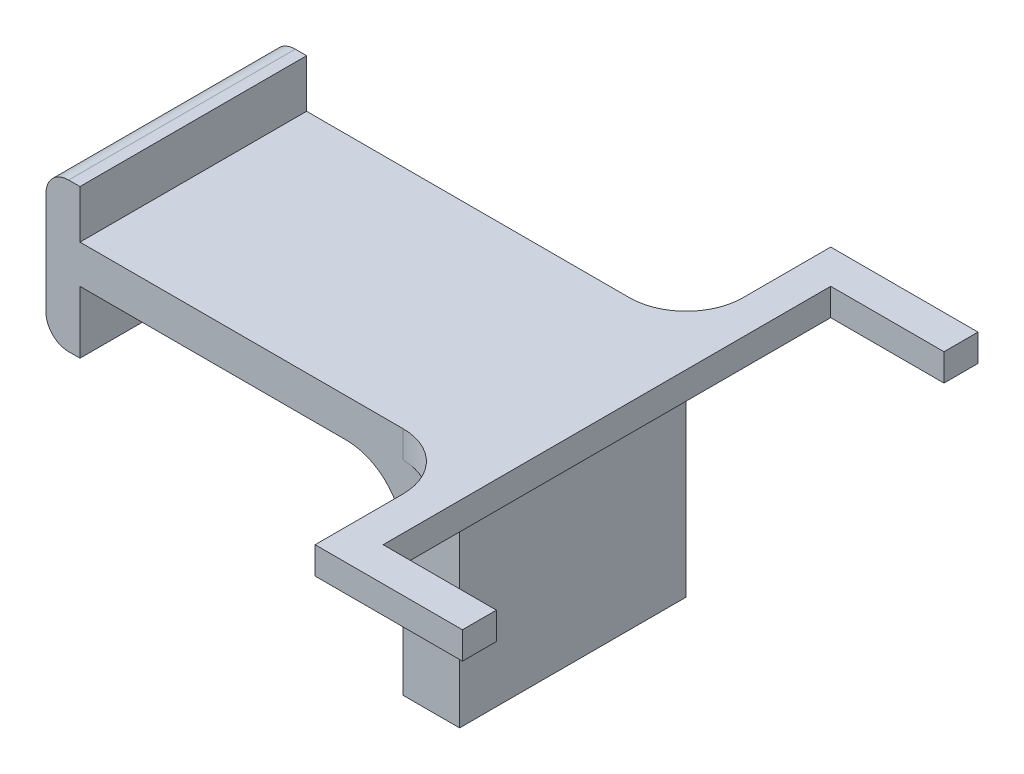
SolidWorks part; units mm, degrees
ref_plane "Front Plane" through (0, 0, 0) normal (0, 0, 1) x (1, 0, 0)
ref_plane "Top Plane" through (0, 0, 0) normal (0, 1, 0) x (1, 0, 0)
ref_plane "Right Plane" through (0, 0, 0) normal (1, 0, 0) x (0, 0, -1)
sketch "Sketch1" plane through (0, 0, 0) normal (0, 1, 0) x (1, 0, 0)
  line L0 (0, 19.75) -> (0, 22.75)
  line L1 (0, 22.75) -> (-13, 22.75)
  line L2 (-13, 22.75) -> (-13, -22.75)
  line L3 (-13, -22.75) -> (0, -22.75)
  line L4 (0, -22.75) -> (0, -19.75)
  line L5 (0, -19.75) -> (-10, -19.75)
  line L6 (-10, -19.75) -> (-10, 19.75)
  line L7 (-10, 19.75) -> (0, 19.75)
  line L9 (-13, 10) -> (-46.5, 10)
  line L10 (-13, 10) -> (-13, -10)
  line L11 (-13, -10) -> (-46.5, -10)
  line L12 (-46.5, 10) -> (-46.5, -10)
  point P7 (-10, 0)
  point P10 (-13, 0)
  dimension "D1" = 45.5
  dimension "D2" = 13
  dimension "D3" = 3
  dimension "D4" = 3
  dimension "D5" = 3
  dimension "D6" = 36.5
  dimension "D7" = 20
extrude "Boss-Extrude1" add sketch "Sketch1" against normal blind 2.4 contours L9 L12 L11 L2 | L6 L7 L0 L1 L2 L3 L4 L5
sketch "Sketch3" plane through (0, 0, 0) normal (0, 0, 1) x (1, 0, 0)
  line L0 (-13, -2.4) -> (-13, -20.38)
  line L1 (-13, -20.38) -> (-18, -20.38)
  line L2 (-18, -20.38) -> (-18, -3.38)
  line L3 (-46.5, -3.38) -> (-46.5, -8.875)
  line L4 (-46.5, -8.875) -> (-49.5, -8.875)
  line L5 (-49.5, -8.875) -> (-49.5, 4.25)
  line L6 (-49.5, 4.25) -> (-46.5, 4.25)
  line L7 (-46.5, 4.25) -> (-46.5, -2.4)
  line L8 (-46.5, -2.4) -> (-13, -2.4)
  line L9 (-13, -2.4) -> (-13, 0) construction
  line L10 (-46.5, -3.38) -> (-18, -3.38)
  line L11 (-46.5, -2.4) -> (-46.5, 0) construction
  dimension "D1" = 0.98
  dimension "D2" = 5
  dimension "D3" = 5.495
  dimension "D4" = 3
  dimension "D5" = 17.98
  dimension "D6" = 6.65
extrude "Boss-Extrude2" add sketch "Sketch3" along normal mid plane 20 contours L0 L1 L2 L10 L3 L4 L5 L6 L7 L8
fillet "Fillet1" radius 5 2 edges at (-13, -1.2, -10) (-13, -1.2, 10)
fillet "Fillet2" radius 5 1 edges at (-18, -3.38, 0)
fillet "Fillet3" radius 2 2 edges at (-49.5, -8.875, 0) (-49.5, 4.25, 0)
